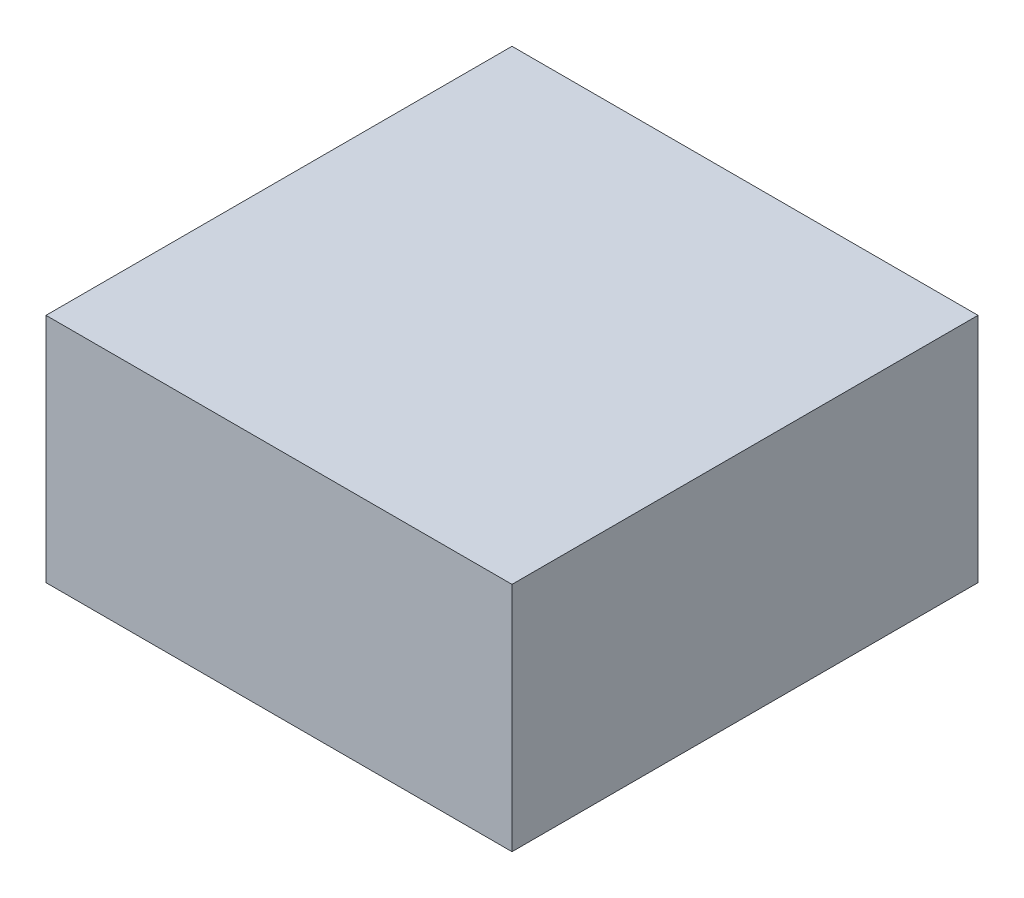
SolidWorks part; units mm, degrees
ref_plane "Front" through (0, 0, 0) normal (0, 0, 1) x (1, 0, 0)
ref_plane "Top" through (0, 0, 0) normal (0, 1, 0) x (1, 0, 0)
ref_plane "Right" through (0, 0, 0) normal (1, 0, 0) x (0, 0, -1)
sketch "Sketch1" plane through (0, 0, 0) normal (0, 1, 0) x (1, 0, 0)
  line L0 (0, 0) -> (203.2, 0)
  line L1 (203.2, 0) -> (203.2, -203.2)
  line L2 (203.2, -203.2) -> (0, -203.2)
  line L3 (0, -203.2) -> (0, 0)
extrude "Boss-Extrude1" add sketch "Sketch1" along normal blind 2.54
sketch "Sketch2" plane through (0, 0, 0) normal (0, -1, 0) x (1, 0, 0)
  line L4 (0, 0) -> (0, 203.2)
  line L5 (0, 203.2) -> (203.2, 203.2) construction
  line L6 (0, 0) -> (0, 203.2) construction
  line L7 (0, 203.2) -> (203.2, 203.2)
  line L8 (3.175, 200.025) -> (3.175, 3.175)
  line L9 (3.175, 3.175) -> (200.025, 3.175)
  line L10 (200.025, 3.175) -> (200.025, 200.025)
  line L11 (200.025, 200.025) -> (3.175, 200.025)
  line L12 (3.175, 200.025) -> (3.175, 3.175)
  line L13 (3.175, 3.175) -> (200.025, 3.175)
  line L14 (200.025, 3.175) -> (200.025, 200.025)
  line L15 (200.025, 200.025) -> (3.175, 200.025)
  line L16 (203.2, 203.2) -> (203.2, 0) construction
  line L17 (203.2, 203.2) -> (203.2, 0)
  line L18 (203.2, 0) -> (0, 0) construction
  line L19 (203.2, 0) -> (0, 0)
  dimension "D1" = 3.175
extrude "Boss-Extrude2" add sketch "Sketch2" along normal blind 98.425
